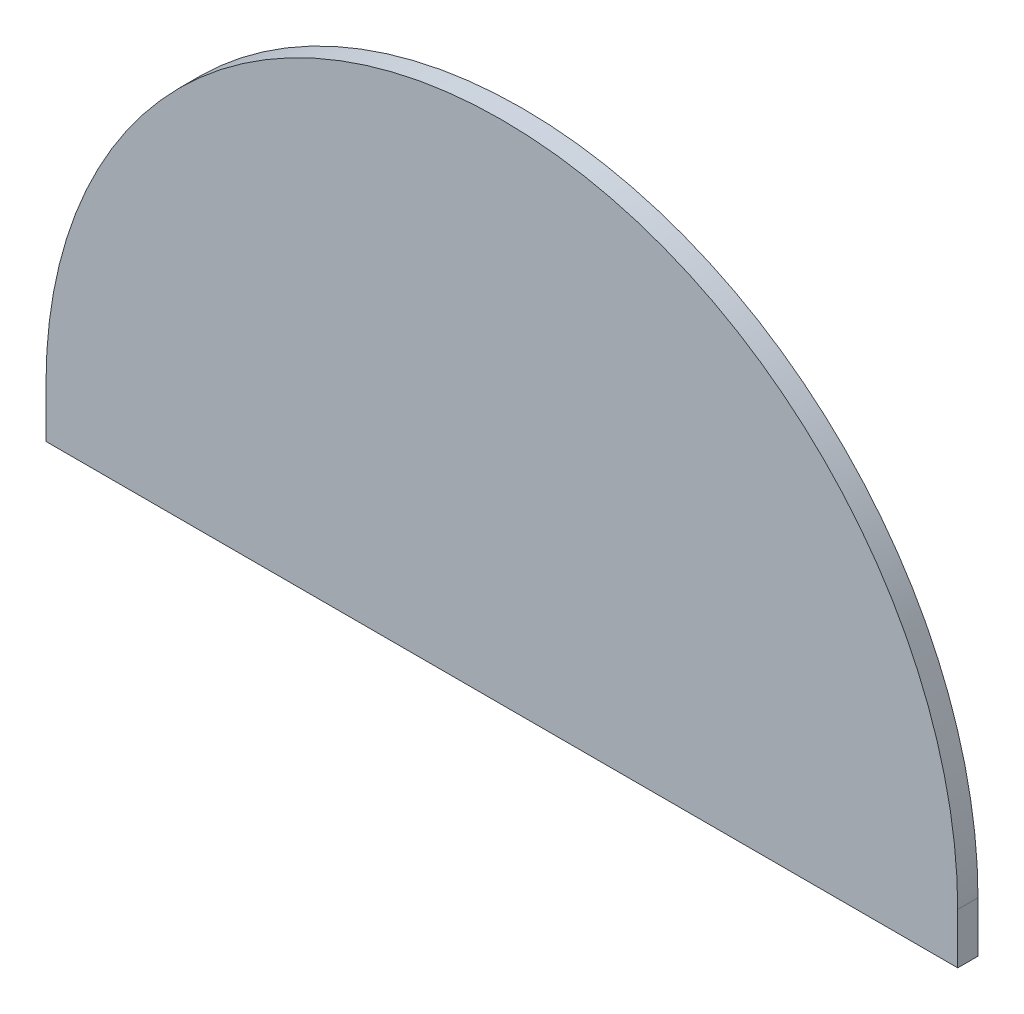
SolidWorks part; units mm, degrees
material "Brass"
ref_plane "Front Plane" through (0, 0, 0) normal (0, 0, 1) x (1, 0, 0)
ref_plane "Top Plane" through (0, 0, 0) normal (0, 1, 0) x (1, 0, 0)
ref_plane "Right Plane" through (0, 0, 0) normal (1, 0, 0) x (0, 0, -1)
sketch "Sketch1" plane through (0, 0, 0) normal (0, 0, 1) x (1, 0, 0)
  line L0 (-45, 0) -> (45, 0)
  arc A0 (-45, 0) -> (45, 0) centre (0, 0) cw
  dimension "D1" = 90
extrude "Boss-Extrude1" add sketch "Sketch1" along normal blind 2
sketch "Sketch2" plane through (0, 0, 0) normal (0, -1, 0) x (1, 0, 0)
  line L1 (45, 2) -> (-45, 2)
  line L2 (45, 2) -> (45, 0)
  line L3 (45, 0) -> (-45, 0)
  line L4 (-45, 2) -> (-45, 0)
extrude "Boss-Extrude2" add sketch "Sketch2" along normal blind 5
